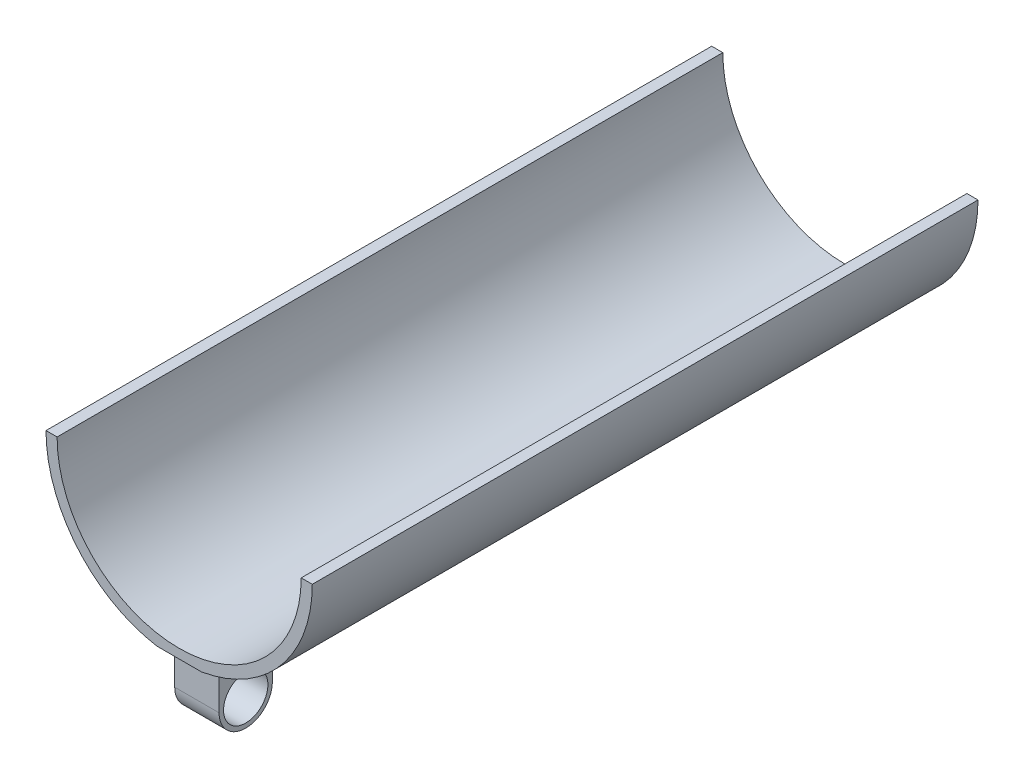
SolidWorks part; units mm, degrees
ref_plane "Front Plane" through (0, 0, 0) normal (0, 0, 1) x (1, 0, 0)
ref_plane "Top Plane" through (0, 0, 0) normal (0, 1, 0) x (1, 0, 0)
ref_plane "Right Plane" through (0, 0, 0) normal (1, 0, 0) x (0, 0, -1)
sketch "Sketch1" plane through (0, 0, 0) normal (0, 0, 1) x (1, 0, 0)
  line L0 (-56.2374, 0) -> (57.613, 0)
  circle A0 centre (0, 0) radius 30
  circle A1 centre (0, 0) radius 27.5
extrude "Boss-Extrude1" add sketch "Sketch1" along normal blind 150 contours A1 L0 A0
sketch "Sketch2" plane through (0, 0, 150) normal (0, 0, 1) x (1, 0, 0)
  line L0 (0, 0) -> (0, -45.4962)
  line L1 (-5, -28) -> (-5, -48)
  line L2 (-5, -28) -> (5, -28)
  line L3 (0, -28) -> (0, -48)
  line L4 (-5, -48) -> (5, -48)
  line L5 (5, -28) -> (5, -48)
  arc A0 (-27.5, 0) -> (27.5, 0) centre (0, 0) ccw construction
  arc M8 (-30, 0) -> (30, 0) centre (0, 0) ccw
  dimension "D1" = 20
  dimension "D2" = 5
  dimension "D3" = 28
extrude "Boss-Extrude2" add sketch "Sketch2" against normal blind 20 contours L1 L4 L3 L0 M8 | L5 L0 L3 L4 M8
sketch "Sketch3" plane through (5, 0, 0) normal (1, 0, 0) x (0, 0, -1)
  line L0 (-130, -29.5804) -> (-150, -29.5804) construction
  line L1 (-130, -29.5804) -> (-130, -48) construction
  circle A0 centre (-140, -39.5804) radius 5
  point P2 (0, 0)
  dimension "D1" = 10
  dimension "D2" = 10
extrude "Cut-Extrude1" cut sketch "Sketch3" against normal blind 20
sketch "Sketch4" plane through (5, 0, 0) normal (1, 0, 0) x (0, 0, -1)
  line L0 (-130, -29.5804) -> (-150, -29.5804) construction
  line L1 (-146, -39.5804) -> (-134, -39.5804)
  line L2 (-146, -39.5804) -> (-146, -29.5804)
  line L3 (-146, -29.5804) -> (-134, -29.5804)
  line L4 (-134, -39.5804) -> (-134, -29.5804)
  line L6 (-150, -29.5804) -> (-130, -29.5804)
  line L7 (-150, -29.5804) -> (-150, -48)
  line L8 (-150, -48) -> (-130, -48)
  line L9 (-130, -29.5804) -> (-130, -48)
  circle A0 centre (-140, -39.5804) radius 6
  line M2 (-150, -29.5804) -> (-150, -48)
  line M3 (-150, -48) -> (-130, -48)
  line M4 (-130, -48) -> (-130, -29.5804)
  line M5 (-130, -29.5804) -> (-150, -29.5804)
extrude "Cut-Extrude2" cut sketch "Sketch4" against normal blind 10 contours A0 L2 L4 M5 M2 M3 M4
